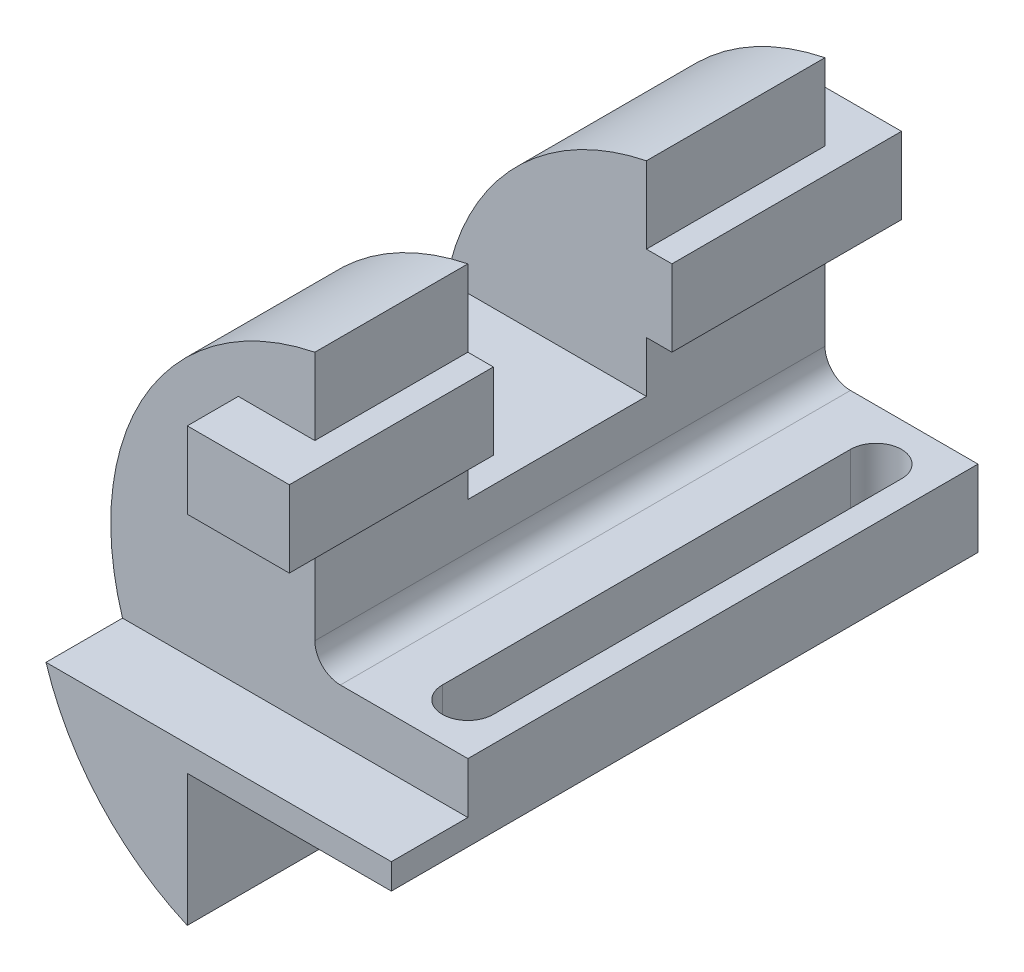
SolidWorks part; units mm, degrees
material "1060 Alloy"
ref_plane "Front Plane" through (0, 0, 0) normal (0, 0, 1) x (1, 0, 0)
ref_plane "Top Plane" through (0, 0, 0) normal (0, 1, 0) x (1, 0, 0)
ref_plane "Right Plane" through (0, 0, 0) normal (1, 0, 0) x (0, 0, -1)
sketch "Sketch1" plane through (0, 0, 0) normal (0, 0, 1) x (1, 0, 0)
  line L0 (0, -106.967) -> (0, 106.967) construction
  line L1 (0, 50) -> (0, -5)
  line L2 (0, -5) -> (20, -5)
  line L3 (20, -5) -> (20, -20)
  line L4 (20, -20) -> (0, -20)
  line L5 (0, -20) -> (0, -50)
  arc A0 (0, 50) -> (0, -50) centre (0, 0) ccw
  point P3 (0, 0)
  point P4 (0, 0)
  dimension "D1" = 100
  dimension "D2" = 15
  dimension "D3" = 55
  dimension "D4" = 20
extrude "Boss-Extrude1" add sketch "Sketch1" against normal blind 115
sketch "Sketch2" plane through (0, 0, 0) normal (0, 0, 1) x (1, 0, 0)
  line L0 (0, -5) -> (-5, -5)
  line L1 (-10, 0) -> (-10, 48.9898)
  line L2 (0, -5) -> (0, 50) construction
  line L3 (0, 50) -> (0, -5)
  arc A0 (0, 50) -> (-10, 48.9898) centre (0, 0) ccw
  arc A1 (0, 50) -> (0, -50) centre (0, 0) ccw construction
  circle A2 centre (-5, 0) radius 5 construction
  arc A3 (-10, 0) -> (-5, -5) centre (-5, 0) ccw
  dimension "D2" = 10
  dimension "D1" = 10
extrude "Cut-Extrude4" cut sketch "Sketch2" against normal blind 115
sketch "Sketch6" plane through (0, 0, 0) normal (0, 0, 1) x (1, 0, 0)
  line L0 (0, -20) -> (-20, -20)
  line L1 (0, -50) -> (0, -20) construction
  line L2 (-20, -20) -> (-20, -45.8258)
  line L3 (0, -20) -> (0, -50)
  arc A0 (-10, 48.9898) -> (0, -50) centre (0, 0) ccw construction
  arc A1 (0, -50) -> (-20, -45.8258) centre (0, 0) cw
  point P12 (-10, -20)
  dimension "D1" = 40
extrude "Cut-Extrude5" cut sketch "Sketch6" against normal blind 115
sketch "Sketch7" plane through (0, 0, 0) normal (0, 0, 1) x (1, 0, 0)
  line L2 (20, -5) -> (-5, -5)
  line L3 (20, -5) -> (-5, -5) construction
  line L4 (-10, 0) -> (-10, 48.9898)
  line L5 (20, -5) -> (20, -15)
  line L6 (20, -20) -> (20, -5) construction
  line L7 (20, -15) -> (-47.697, -15)
  arc A1 (-10, 0) -> (-5, -5) centre (-5, 0) ccw construction
  arc A2 (-10, 0) -> (-5, -5) centre (-5, 0) ccw
  arc A3 (-10, 48.9898) -> (-47.697, -15) centre (0, 0) ccw
  dimension "D1" = 10
extrude "Cut-Extrude7" cut sketch "Sketch7" against normal blind 15
sketch "Sketch8" plane through (-10, 0, 0) normal (1, 0, 0) x (0, 0, -1)
  line L0 (115, 48.9898) -> (15, 48.9898) construction
  line L1 (45, 48.9898) -> (80, 48.9898)
  line L2 (45, 48.9898) -> (45, 8.9898)
  line L3 (45, 8.9898) -> (80, 8.9898)
  line L4 (80, 48.9898) -> (80, 8.9898)
  line L5 (15, 0) -> (15, 48.9898) construction
  dimension "D1" = 40
  dimension "D2" = 30
  dimension "D3" = 35
extrude "Cut-Extrude8" cut sketch "Sketch8" against normal blind 55
sketch "Sketch9" plane through (0, 0, -15) normal (0, 0, 1) x (1, 0, 0)
  line L0 (-10, 8.9898) -> (-49.1852, 8.9898) construction
  line L1 (-10, 0) -> (-10, 48.9898) construction
  line L3 (-25, 33.9898) -> (-5, 33.9898)
  line L4 (-25, 33.9898) -> (-25, 18.9898)
  line L5 (-25, 18.9898) -> (-5, 18.9898)
  line L6 (-5, 33.9898) -> (-5, 18.9898)
  arc A0 (-10, 48.9898) -> (-47.697, -15) centre (0, 0) ccw construction
  dimension "D1" = 40
  dimension "D2" = 5
  dimension "D3" = 20
  dimension "D4" = 15
  dimension "D5" = 15
extrude "Boss-Extrude2" add sketch "Sketch9" against normal blind 30 and the other way blind 10
sketch "Sketch10" plane through (0, 0, -115) normal (0, 0, -1) x (-1, 0, 0)
  line L0 (10, 8.9898) -> (49.1852, 8.9898)
  line L1 (10, 48.9898) -> (10, 0) construction
  line L3 (5, 33.9898) -> (25, 33.9898)
  line L4 (5, 33.9898) -> (5, 18.9898)
  line L5 (5, 18.9898) -> (25, 18.9898)
  line L6 (25, 33.9898) -> (25, 18.9898)
  arc A0 (20, -45.8258) -> (10, 48.9898) centre (0, 0) ccw construction
  line M8 (10, 48.9898) -> (10, 0)
  dimension "D1" = 40
  dimension "D2" = 15
  dimension "D3" = 10
  dimension "D4" = 15
extrude "Boss-Extrude4" add sketch "Sketch10" against normal blind 35 and the other way blind 10 contours L6 L3 L5 M8 | L4 L5 L3 M8
sketch "Sketch11" plane through (0, -5, 0) normal (0, 1, 0) x (1, 0, 0)
  line L0 (-47.697, 15) -> (20, 15) construction
  line L1 (20, 115) -> (-5, 115) construction
  line L2 (20, 115) -> (20, 15) construction
  line L3 (5, 105) -> (5, 25)
  line L4 (15, 105) -> (15, 25)
  arc A0 (5, 25) -> (15, 25) centre (10, 25) ccw
  arc A1 (15, 105) -> (5, 105) centre (10, 105) ccw
  dimension "D1" = 10
  dimension "D2" = 10
  dimension "D3" = 10
  dimension "D4" = 10
  dimension "D5" = 10
  dimension "D6" = 10
extrude "Cut-Extrude9" cut sketch "Sketch11" against normal blind 35
